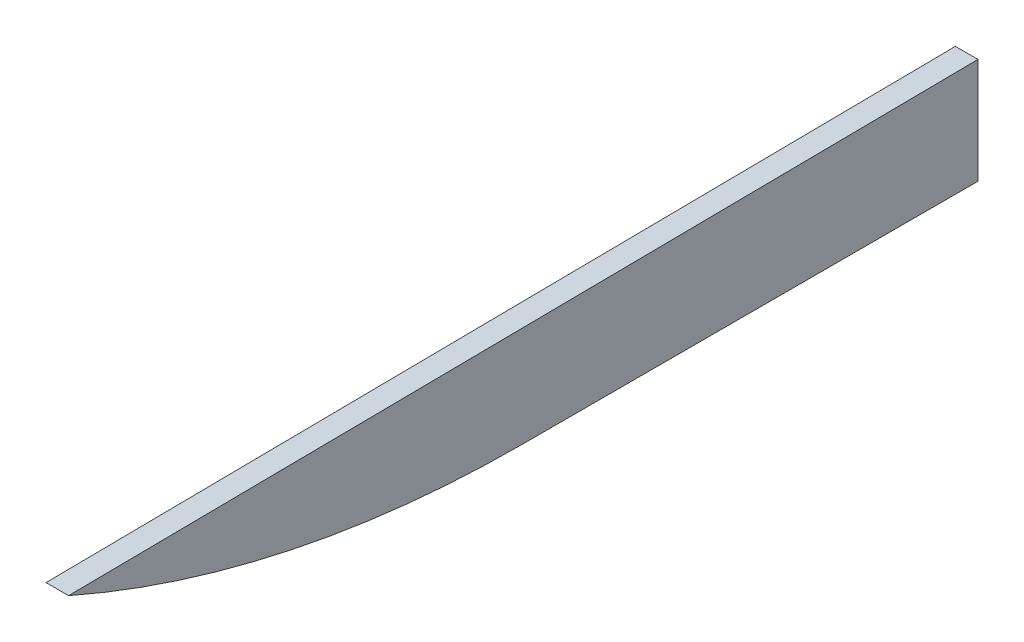
SolidWorks part; units mm, degrees
ref_plane "Front Plane" through (0, 0, 0) normal (0, 0, 1) x (1, 0, 0)
ref_plane "Top Plane" through (0, 0, 0) normal (0, 1, 0) x (1, 0, 0)
ref_plane "Right Plane" through (0, 0, 0) normal (1, 0, 0) x (0, 0, -1)
sketch "Sketch1" plane through (0, 0, 0) normal (1, 0, 0) x (0, 0, -1)
  line L0 (-69.3618, 16.1414) -> (51.4679, 17.4327)
  line L1 (51.4679, 17.4327) -> (51.4679, 3.4127)
  line L2 (51.4679, 3.4127) -> (-8.9469, 3.4127)
  arc A0 (-8.9469, 3.4127) -> (-69.3618, 16.1414) centre (-8.9469, 153.153) cw
extrude "Boss-Extrude1" add sketch "Sketch1" along normal mid plane 3
